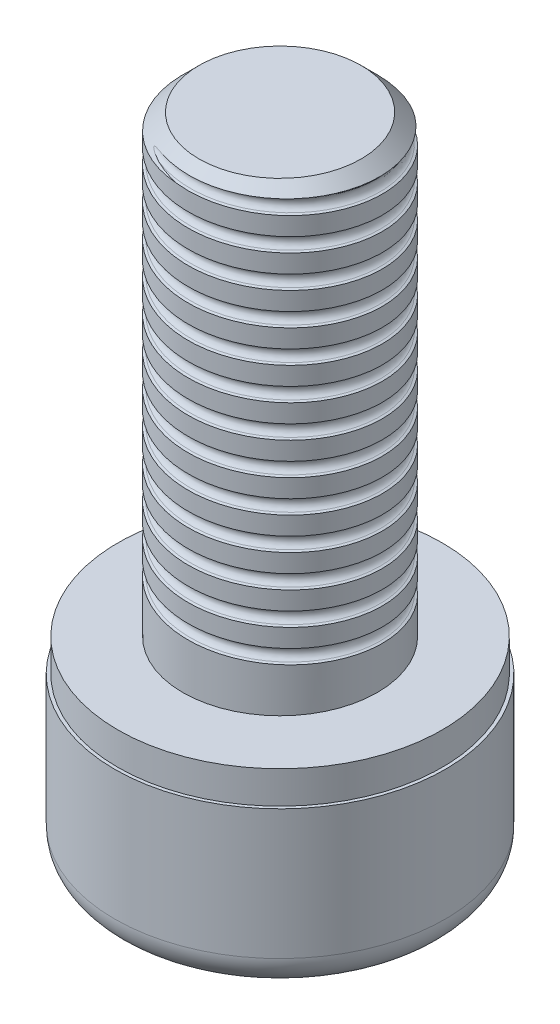
SolidWorks part; units mm, degrees
ref_plane "Спереди" through (0, 0, 0) normal (0, 0, 1) x (1, 0, 0)
ref_plane "Сверху" through (0, 0, 0) normal (0, 1, 0) x (1, 0, 0)
ref_plane "Справа" through (0, 0, 0) normal (1, 0, 0) x (0, 0, -1)
sketch "Эскиз1" plane through (0, 0, 0) normal (0, 1, 0) x (1, 0, 0)
  circle A0 centre (0, 0) radius 5.1
  dimension "D1" = 10.2
extrude "Бобышка-Вытянуть1" add sketch "Эскиз1" along normal blind 6
sketch "Эскиз2" plane through (0, 6, 0) normal (0, 1, 0) x (1, 0, 0)
  circle A0 centre (0, 0) radius 3
  dimension "D1" = 6
extrude "Бобышка-Вытянуть2" add sketch "Эскиз2" along normal blind 14
chamfer "Фаска1" distance 0.5 angle 45 1 edges at (0, 20, 3)
sketch "Эскиз3" plane through (0, 0, 0) normal (0, -1, 0) x (1, 0, 0)
  line L1 (2.5363, -1.4958) -> (2.5635, 1.4486)
  line L2 (2.5635, 1.4486) -> (0.0272, 2.9444)
  line L3 (0.0272, 2.9444) -> (-2.5363, 1.4958)
  line L4 (-2.5363, 1.4958) -> (-2.5635, -1.4486)
  line L5 (-2.5635, -1.4486) -> (-0.0272, -2.9444)
  line L6 (-0.0272, -2.9444) -> (2.5363, -1.4958)
  circle A0 centre (0, 0) radius 2.55 construction
  dimension "D1" = 5.1
extrude "Вырез-Вытянуть1" cut sketch "Эскиз3" against normal blind 2.5
fillet "Скругление1" radius 1 1 edges at (0, 0, 5.1)
sketch "Эскиз4" plane through (0, 6, 0) normal (0, 1, 0) x (1, 0, 0)
  circle A0 centre (0, 0) radius 5
  circle A1 centre (0, 0) radius 5.1
  circle A2 centre (0, 0) radius 5.1 construction
  dimension "D1" = 10
sketch "Эскиз7" plane through (0, 20, 0) normal (0, 1, 0) x (1, 0, 0)
  circle A0 centre (0, 0) radius 2.5
ref_plane "Плоскость2" through (0, 19.5, 0) normal (0, -1, 0) x (-1, 0, 0)
sketch "Эскиз8" plane through (0, 19.5, 0) normal (0, -1, 0) x (-1, 0, 0)
  circle A0 centre (0, 0) radius 3
  circle A1 centre (0, 0) radius 3 construction
curve "Спираль2" pitch 1 height 12.75 turns 12.75
sketch "Эскиз10" plane through (0, 0, 0) normal (0, 0, 1) x (1, 0, 0)
  line L0 (3.4, 16.8228) -> (3.4, 16.0949)
  line L1 (3.4, 16.0949) -> (2.9298, 16.266)
  line L2 (2.9298, 16.6517) -> (3.4, 16.8228)
  line L3 (3.4, 16.4589) -> (2.7948, 16.4589) construction
  arc A0 (2.9298, 16.6517) -> (2.9298, 16.266) centre (3, 16.4589) ccw
  dimension "D1" = 40
  dimension "D2" = 0.4702
  dimension "D3" = 0.4
  dimension "D4" = 3.4
sweep "Вырез-По траектории1" cut profiles "Эскиз10" path "Спираль2"
extrude "Вырез-Вытянуть2" cut sketch "Эскиз4" against normal blind 1
